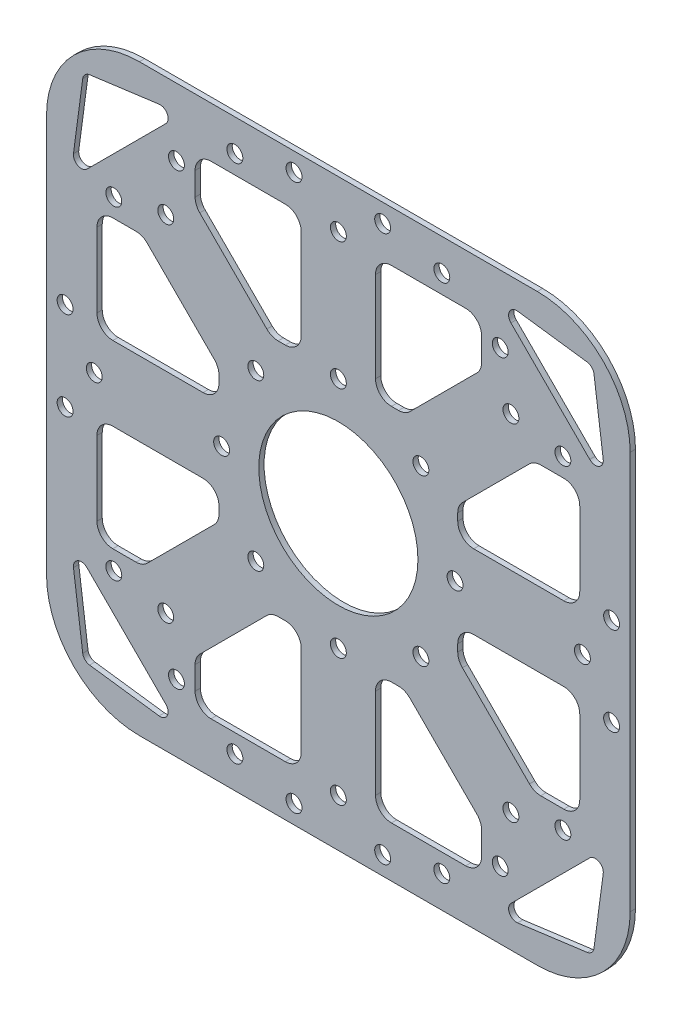
SolidWorks part; units mm, degrees
material "Fibra de vidrio-A"
ref_plane "Alzado" through (0, 0, 0) normal (0, 0, 1) x (1, 0, 0)
ref_plane "Planta" through (0, 0, 0) normal (0, 1, 0) x (1, 0, 0)
ref_plane "Vista lateral" through (0, 0, 0) normal (1, 0, 0) x (0, 0, -1)
sketch "Croquis1" plane through (0, 0, 0) normal (0, 0, 1) x (1, 0, 0)
  line L1 (17.5, 0) -> (92.5, 0)
  line L2 (0, 17.5) -> (0, 92.5)
  line L3 (17.5, 110) -> (92.5, 110)
  line L4 (110, 17.5) -> (110, 92.5)
  arc A0 (92.5, 110) -> (110, 92.5) centre (92.5, 92.5) cw
  arc A1 (92.5, 0) -> (110, 17.5) centre (92.5, 17.5) ccw
  arc A2 (17.5, 0) -> (0, 17.5) centre (17.5, 17.5) cw
  arc A3 (0, 92.5) -> (17.5, 110) centre (17.5, 92.5) cw
  point P11 (0, 0)
  point P14 (0, 110)
  dimension "D2" = 17.5
  dimension "D3" = 17.5
  dimension "D1" = 110
extrude "Saliente-Extruir1" add sketch "Croquis1" against normal blind 1
sketch "Croquis3" plane through (0, 0, 0) normal (0, 0, 1) x (1, 0, 0)
  line L0 (106.4853, 106.4853) -> (3.5147, 3.5147) construction
  line L1 (55, 55) -> (33.0263, 76.9737) construction
  line L2 (16.2626, 55) -> (93.7374, 55) construction
  line L3 (55, 55) -> (55, 120.4186) construction
  circle A0 centre (77, 55) radius 1.5
  circle A1 centre (55, 55) radius 15
  circle A2 centre (70.5563, 70.5563) radius 1.5
  circle A3 centre (87.5269, 87.5269) radius 1.5
  circle A4 centre (101, 55) radius 1.5
  circle A5 centre (70.5563, 39.4437) radius 1.5
  circle A6 centre (87.5269, 22.4731) radius 1.5
  circle A7 centre (55, 33) radius 1.5
  circle A8 centre (55, 9) radius 1.5
  circle A9 centre (39.4437, 39.4437) radius 1.5
  circle A10 centre (22.4731, 22.4731) radius 1.5
  circle A11 centre (33, 55) radius 1.5
  circle A12 centre (9, 55) radius 1.5
  circle A13 centre (39.4437, 70.5563) radius 1.5
  circle A14 centre (22.4731, 87.5269) radius 1.5
  circle A15 centre (55, 77) radius 1.5
  circle A16 centre (55, 101) radius 1.5
  point P6 (55, 55)
  point P14 (55, 55)
  point P46 (55, 55)
  dimension "D1" = 30
  dimension "D2" = 3
  dimension "D3" = 22
  dimension "D4" = 24
  dimension "D5" = 8
extrude "Cortar-Extruir1" cut sketch "Croquis3" against normal blind 1
sketch "Croquis4" plane through (0, 0, 0) normal (0, 0, 1) x (1, 0, 0)
  line L0 (55, 55) -> (55, 110) construction
  line L1 (92.5, 110) -> (17.5, 110) construction
  line L2 (62, 97.5) -> (62, 80.5)
  line L3 (65, 100.5) -> (79, 100.5)
  line L4 (55, 55) -> (104.8744, 104.8744) construction
  line L5 (68.4792, 78.3787) -> (81.1213, 91.0208)
  line L6 (65, 77.5) -> (66.3579, 77.5)
  line L7 (82, 97.5) -> (82, 93.1421)
  line L8 (77.5, 65) -> (77.5, 66.3579)
  line L9 (97.5, 62) -> (80.5, 62)
  line L10 (100.5, 65) -> (100.5, 79)
  line L11 (97.5, 82) -> (93.1421, 82)
  line L12 (78.3787, 68.4792) -> (91.0208, 81.1213)
  line L13 (78.3787, 41.5208) -> (91.0208, 28.8787)
  line L14 (97.5, 28) -> (93.1421, 28)
  line L15 (100.5, 45) -> (100.5, 31)
  line L16 (97.5, 48) -> (80.5, 48)
  line L17 (77.5, 45) -> (77.5, 43.6421)
  line L18 (65, 32.5) -> (66.3579, 32.5)
  line L19 (68.4792, 31.6213) -> (81.1213, 18.9792)
  line L20 (82, 12.5) -> (82, 16.8579)
  line L21 (65, 9.5) -> (79, 9.5)
  line L22 (62, 12.5) -> (62, 29.5)
  line L23 (41.5208, 31.6213) -> (28.8787, 18.9792)
  line L24 (28, 12.5) -> (28, 16.8579)
  line L25 (45, 9.5) -> (31, 9.5)
  line L26 (48, 12.5) -> (48, 29.5)
  line L27 (45, 32.5) -> (43.6421, 32.5)
  line L28 (32.5, 45) -> (32.5, 43.6421)
  line L29 (31.6213, 41.5208) -> (18.9792, 28.8787)
  line L30 (12.5, 28) -> (16.8579, 28)
  line L31 (9.5, 45) -> (9.5, 31)
  line L32 (12.5, 48) -> (29.5, 48)
  line L33 (31.6213, 68.4792) -> (18.9792, 81.1213)
  line L34 (12.5, 82) -> (16.8579, 82)
  line L35 (9.5, 65) -> (9.5, 79)
  line L36 (12.5, 62) -> (29.5, 62)
  line L37 (32.5, 65) -> (32.5, 66.3579)
  line L38 (45, 77.5) -> (43.6421, 77.5)
  line L39 (41.5208, 78.3787) -> (28.8787, 91.0208)
  line L40 (28, 97.5) -> (28, 93.1421)
  line L41 (45, 100.5) -> (31, 100.5)
  line L42 (48, 97.5) -> (48, 80.5)
  arc A0 (110, 92.5) -> (92.5, 110) centre (92.5, 92.5) ccw construction
  arc A1 (79, 100.5) -> (82, 97.5) centre (79, 97.5) cw
  arc A2 (81.1213, 91.0208) -> (82, 93.1421) centre (79, 93.1421) ccw
  arc A3 (68.4792, 78.3787) -> (66.3579, 77.5) centre (66.3579, 80.5) cw
  arc A4 (62, 80.5) -> (65, 77.5) centre (65, 80.5) ccw
  arc A5 (62, 97.5) -> (65, 100.5) centre (65, 97.5) cw
  arc A6 (80.5, 62) -> (77.5, 65) centre (80.5, 65) cw
  arc A7 (97.5, 62) -> (100.5, 65) centre (97.5, 65) ccw
  arc A8 (100.5, 79) -> (97.5, 82) centre (97.5, 79) ccw
  arc A9 (91.0208, 81.1213) -> (93.1421, 82) centre (93.1421, 79) cw
  arc A10 (78.3787, 68.4792) -> (77.5, 66.3579) centre (80.5, 66.3579) ccw
  arc A11 (78.3787, 41.5208) -> (77.5, 43.6421) centre (80.5, 43.6421) cw
  arc A12 (91.0208, 28.8787) -> (93.1421, 28) centre (93.1421, 31) ccw
  arc A13 (100.5, 31) -> (97.5, 28) centre (97.5, 31) cw
  arc A14 (97.5, 48) -> (100.5, 45) centre (97.5, 45) cw
  arc A15 (80.5, 48) -> (77.5, 45) centre (80.5, 45) ccw
  arc A16 (68.4792, 31.6213) -> (66.3579, 32.5) centre (66.3579, 29.5) ccw
  arc A17 (81.1213, 18.9792) -> (82, 16.8579) centre (79, 16.8579) cw
  arc A18 (79, 9.5) -> (82, 12.5) centre (79, 12.5) ccw
  arc A19 (62, 12.5) -> (65, 9.5) centre (65, 12.5) ccw
  arc A20 (62, 29.5) -> (65, 32.5) centre (65, 29.5) cw
  arc A21 (41.5208, 31.6213) -> (43.6421, 32.5) centre (43.6421, 29.5) cw
  arc A22 (28.8787, 18.9792) -> (28, 16.8579) centre (31, 16.8579) ccw
  arc A23 (31, 9.5) -> (28, 12.5) centre (31, 12.5) cw
  arc A24 (48, 12.5) -> (45, 9.5) centre (45, 12.5) cw
  arc A25 (48, 29.5) -> (45, 32.5) centre (45, 29.5) ccw
  arc A26 (31.6213, 41.5208) -> (32.5, 43.6421) centre (29.5, 43.6421) ccw
  arc A27 (18.9792, 28.8787) -> (16.8579, 28) centre (16.8579, 31) cw
  arc A28 (9.5, 31) -> (12.5, 28) centre (12.5, 31) ccw
  arc A29 (12.5, 48) -> (9.5, 45) centre (12.5, 45) ccw
  arc A30 (29.5, 48) -> (32.5, 45) centre (29.5, 45) cw
  arc A31 (31.6213, 68.4792) -> (32.5, 66.3579) centre (29.5, 66.3579) cw
  arc A32 (18.9792, 81.1213) -> (16.8579, 82) centre (16.8579, 79) ccw
  arc A33 (9.5, 79) -> (12.5, 82) centre (12.5, 79) cw
  arc A34 (12.5, 62) -> (9.5, 65) centre (12.5, 65) cw
  arc A35 (29.5, 62) -> (32.5, 65) centre (29.5, 65) ccw
  arc A36 (41.5208, 78.3787) -> (43.6421, 77.5) centre (43.6421, 80.5) ccw
  arc A37 (28.8787, 91.0208) -> (28, 93.1421) centre (31, 93.1421) cw
  arc A38 (31, 100.5) -> (28, 97.5) centre (31, 97.5) ccw
  arc A39 (48, 97.5) -> (45, 100.5) centre (45, 97.5) ccw
  arc A40 (48, 80.5) -> (45, 77.5) centre (45, 80.5) cw
  point P16 (82, 100.5)
  point P25 (62, 100.5)
  point P134 (55, 55)
  dimension "D5" = 3
  dimension "D1" = 14
  dimension "D2" = 9.5
  dimension "D3" = 20
  dimension "D4" = 14
  dimension "D7" = 23
  dimension "D6" = 4
extrude "Cortar-Extruir2" cut sketch "Croquis4" against normal blind 1
sketch "Croquis5" plane through (0, 0, 0) normal (0, 0, 1) x (1, 0, 0)
  line L0 (92.5, 110) -> (17.5, 110) construction
  line L1 (55, 55) -> (55, 110) construction
  circle A0 centre (63.3516, 106.5) radius 1.5
  circle A17 centre (55, 101) radius 1.5 construction
  circle A20 centre (46.6484, 106.5) radius 1.5
  circle A27 centre (85.5105, 97.3215) radius 1.5
  circle A28 centre (97.3215, 85.5105) radius 1.5
  circle A29 centre (106.5, 63.3516) radius 1.5
  circle A30 centre (106.5, 46.6484) radius 1.5
  circle A31 centre (97.3215, 24.4895) radius 1.5
  circle A32 centre (85.5105, 12.6785) radius 1.5
  circle A33 centre (63.3516, 3.5) radius 1.5
  circle A34 centre (46.6484, 3.5) radius 1.5
  circle A35 centre (24.4895, 12.6785) radius 1.5
  circle A36 centre (12.6785, 24.4895) radius 1.5
  circle A37 centre (3.5, 46.6484) radius 1.5
  circle A38 centre (3.5, 63.3516) radius 1.5
  circle A39 centre (12.6785, 85.5105) radius 1.5
  circle A40 centre (24.4895, 97.3215) radius 1.5
  point P26 (55, 55)
  point P43 (55, 55)
  dimension "D1" = 3
  dimension "D3" = 3.5
  dimension "D2" = 10
extrude "Cortar-Extruir3" cut sketch "Croquis5" against normal blind 1
sketch "Croquis7" plane through (0, 0, 0) normal (0, 0, 1) x (1, 0, 0)
  line L0 (55, 55) -> (104.8744, 104.8744) construction
  line L1 (87.5269, 102.3762) -> (102.3762, 87.5269)
  line L2 (104.9237, 88.7855) -> (103.1793, 101.8903)
  line L3 (88.7855, 104.9237) -> (101.8903, 103.1793)
  line L4 (102.3762, 22.4731) -> (87.5269, 7.6238)
  line L5 (88.7855, 5.0763) -> (101.8903, 6.8207)
  line L6 (104.9237, 21.2145) -> (103.1793, 8.1097)
  line L7 (55, 55) -> (104.8744, 5.1256) construction
  line L8 (22.4731, 7.6238) -> (7.6238, 22.4731)
  line L9 (5.0763, 21.2145) -> (6.8207, 8.1097)
  line L10 (21.2145, 5.0763) -> (8.1097, 6.8207)
  line L11 (55, 55) -> (5.1256, 5.1256) construction
  line L12 (7.6238, 87.5269) -> (22.4731, 102.3762)
  line L13 (21.2145, 104.9237) -> (8.1097, 103.1793)
  line L14 (5.0763, 88.7855) -> (6.8207, 101.8903)
  line L15 (55, 55) -> (5.1256, 104.8744) construction
  arc A0 (110, 92.5) -> (92.5, 110) centre (92.5, 92.5) ccw construction
  arc A2 (102.3762, 87.5269) -> (104.9237, 88.7855) centre (103.4368, 88.5876) ccw
  arc A3 (103.1793, 101.8903) -> (101.8903, 103.1793) centre (101.6924, 101.6924) ccw
  circle A4 centre (87.5269, 87.5269) radius 1.5 construction
  arc A5 (87.5269, 102.3762) -> (88.7855, 104.9237) centre (88.5876, 103.4368) cw
  arc A6 (87.5269, 7.6238) -> (88.7855, 5.0763) centre (88.5876, 6.5632) ccw
  arc A7 (101.8903, 6.8207) -> (103.1793, 8.1097) centre (101.6924, 8.3076) ccw
  arc A8 (102.3762, 22.4731) -> (104.9237, 21.2145) centre (103.4368, 21.4124) cw
  arc A9 (7.6238, 22.4731) -> (5.0763, 21.2145) centre (6.5632, 21.4124) ccw
  arc A10 (6.8207, 8.1097) -> (8.1097, 6.8207) centre (8.3076, 8.3076) ccw
  arc A11 (22.4731, 7.6238) -> (21.2145, 5.0763) centre (21.4124, 6.5632) cw
  arc A12 (22.4731, 102.3762) -> (21.2145, 104.9237) centre (21.4124, 103.4368) ccw
  arc A13 (8.1097, 103.1793) -> (6.8207, 101.8903) centre (8.3076, 101.6924) ccw
  arc A14 (7.6238, 87.5269) -> (5.0763, 88.7855) centre (6.5632, 88.5876) cw
  point P19 (94.9515, 94.9515)
  point P31 (94.9515, 15.0485)
  point P42 (15.0485, 15.0485)
  point P53 (15.0485, 94.9515)
  point P54 (55, 55)
  dimension "D1" = 3
  dimension "D2" = 3
  dimension "D3" = 4.5
  dimension "D5" = 10.5
  dimension "D4" = 10.5
  dimension "D6" = 4
extrude "Cortar-Extruir4" cut sketch "Croquis7" against normal blind 1
sketch "Croquis8" plane through (0, 0, 0) normal (0, 0, 1) x (1, 0, 0)
  line L0 (79, 100.5) -> (65, 100.5) construction
  line L1 (55, 55) -> (55, 110) construction
  line L2 (92.5, 110) -> (17.5, 110) construction
  line L3 (0, 55) -> (110, 55) construction
  line L4 (0, 92.5) -> (0, 17.5) construction
  line L5 (110, 17.5) -> (110, 92.5) construction
  circle A0 centre (74.5, 104) radius 1.5
  circle A4 centre (35.5, 104) radius 1.5
  circle A5 centre (35.5, 6) radius 1.5
  circle A6 centre (74.5, 6) radius 1.5
  dimension "D1" = 3
  dimension "D3" = 39
  dimension "D2" = 3.5
extrude "Cortar-Extruir5" cut sketch "Croquis8" against normal blind 1
